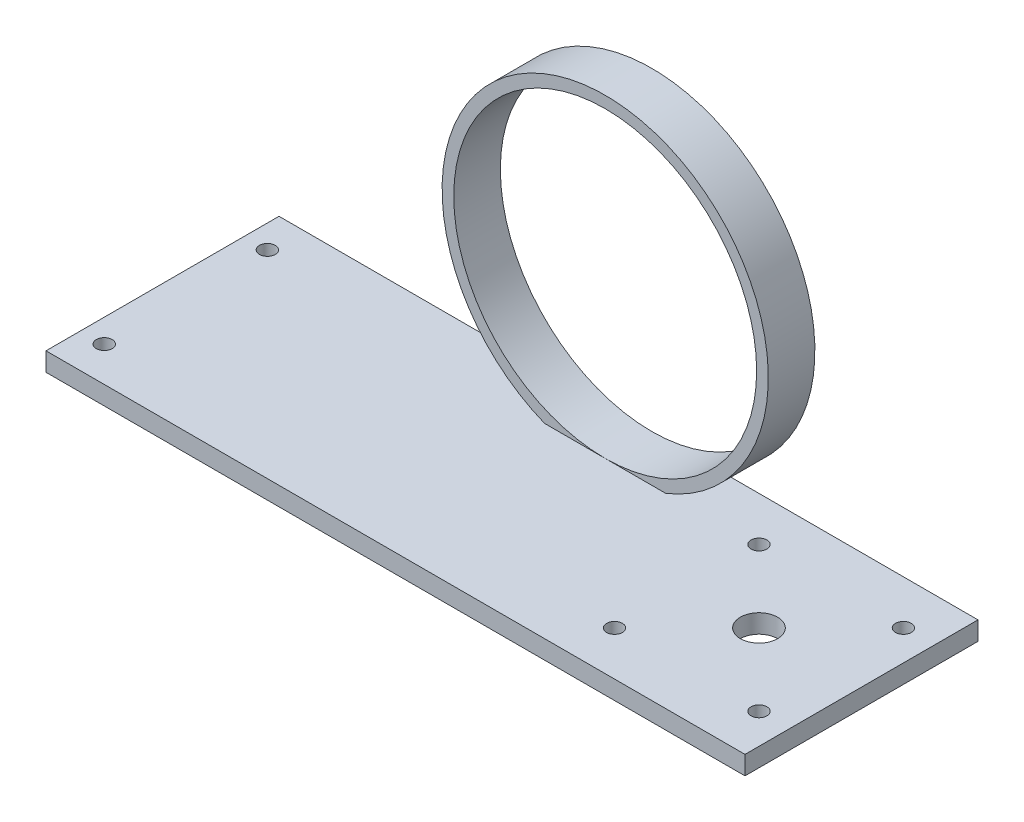
SolidWorks part; units mm, degrees
material "ABS"
ref_plane "正面" through (0, 0, 0) normal (0, 0, 1) x (1, 0, 0)
ref_plane "平面" through (0, 0, 0) normal (0, 1, 0) x (1, 0, 0)
ref_plane "右側面" through (0, 0, 0) normal (1, 0, 0) x (0, 0, -1)
sketch "ｽｹｯﾁ1" plane through (0, 0, 0) normal (0, 0, 1) x (1, 0, 0)
  circle A0 centre (0, 0) radius 32.5
  circle A1 centre (0, 0) radius 35
  dimension "D1" = 70
  dimension "D2" = 65
extrude "ﾎﾞｽ - 押し出し1" add sketch "ｽｹｯﾁ1" along normal blind 10
sketch "ｽｹｯﾁ2" plane through (0, 0, 0) normal (0, 0, -1) x (-1, 0, 0)
  line L0 (0, -32.5) -> (-70, -32.5)
  line L1 (-70, -32.5) -> (-70, -36.5)
  line L2 (-70, -36.5) -> (80, -36.5)
  line L3 (0, -32.5) -> (80, -32.5)
  line L4 (80, -32.5) -> (80, -36.5)
  circle A0 centre (0, 0) radius 32.5 construction
  dimension "D1" = 4
  dimension "D2" = 70
  dimension "D3" = 80
extrude "ﾎﾞｽ - 押し出し2" add sketch "ｽｹｯﾁ2" against normal blind 50
sketch "ｽｹｯﾁ3" plane through (0, -32.5, 0) normal (0, 1, 0) x (1, 0, 0)
  line L0 (48, 0) -> (48, -50) construction
  line L1 (12.9904, 0) -> (70, 0) construction
  line L2 (-80, -50) -> (70, -50) construction
  line L3 (70, -50) -> (70, 0) construction
  circle A0 centre (48, -25) radius 4
  dimension "D2" = 8
  dimension "D1" = 22
extrude "ｶｯﾄ - 押し出し1" cut sketch "ｽｹｯﾁ3" against normal up to next
sketch "ｽｹｯﾁ4" plane through (0, -36.5, 0) normal (0, -1, 0) x (1, 0, 0)
  line L0 (48, 25) -> (48, 0) construction
  line L1 (70, 0) -> (-80, 0) construction
  line L2 (48, 25) -> (70, 25) construction
  line L3 (70, 50) -> (70, 0) construction
  line L4 (63.5, 40.5) -> (63.5, 9.5) construction
  line L5 (63.5, 9.5) -> (32.5, 9.5) construction
  line L6 (32.5, 9.5) -> (32.5, 40.5) construction
  line L7 (32.5, 40.5) -> (63.5, 40.5) construction
  circle A0 centre (63.5, 40.5) radius 1.7
  circle A1 centre (63.5, 9.5) radius 1.7
  circle A2 centre (32.5, 40.5) radius 1.7
  circle A3 centre (32.5, 9.5) radius 1.7
  arc A4 (60.75, 40.5) -> (66.25, 40.5) centre (63.5, 40.5) ccw construction
  point P12 (63.5, 25)
  point P13 (48, 9.5)
  point P18 (0, 0)
  dimension "D2" = 3.4
  dimension "D3" = 3.4
extrude "ｶｯﾄ - 押し出し2" cut sketch "ｽｹｯﾁ4" against normal up to next
sketch "ｽｹｯﾁ5" plane through (0, -36.5, 0) normal (0, -1, 0) x (1, 0, 0)
  line L0 (70, 25) -> (-80, 25) construction
  line L4 (-75, 42.5) -> (-75, 7.5) construction
  line L5 (70, 50) -> (70, 0) construction
  line L6 (-80, 50) -> (-80, 0) construction
  circle A0 centre (-75, 42.5) radius 1.7
  circle A1 centre (-75, 7.5) radius 1.7
  point P6 (-75, 25)
  dimension "D2" = 3.4
  dimension "D1" = 5
  dimension "D3" = 35
extrude "ｶｯﾄ - 押し出し3" cut sketch "ｽｹｯﾁ5" against normal up to next
